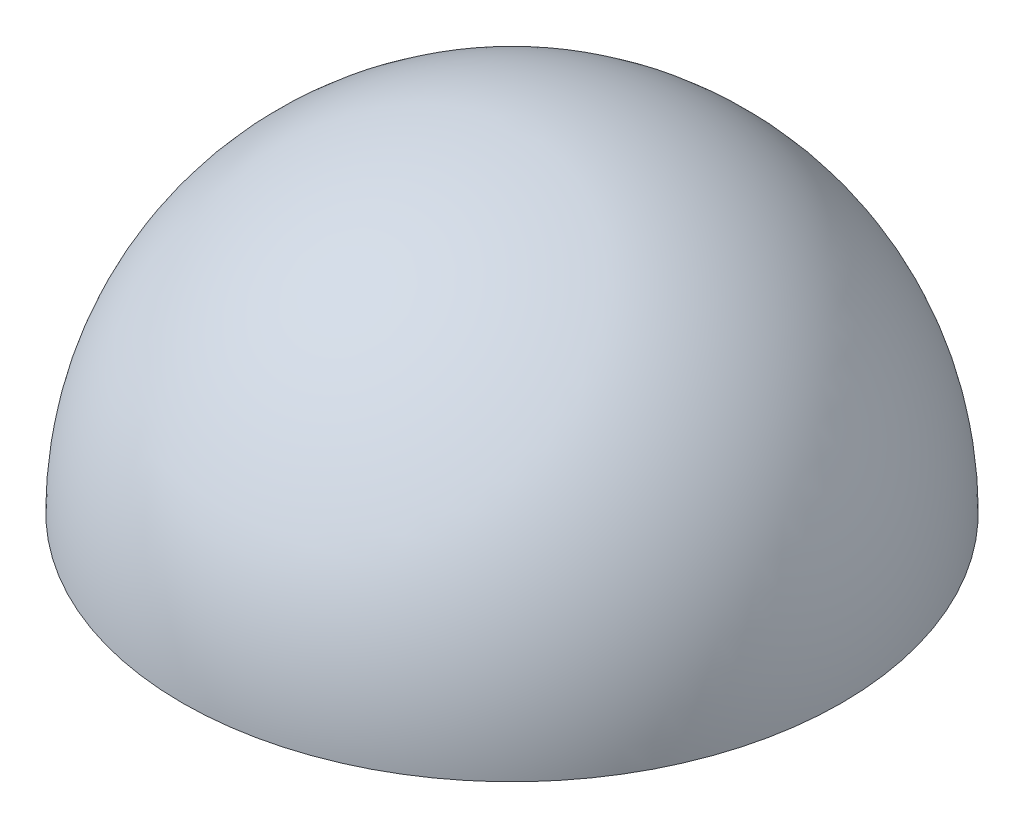
SolidWorks part; units mm, degrees
ref_plane "Front Plane" through (0, 0, 0) normal (0, 0, 1) x (1, 0, 0)
ref_plane "Top Plane" through (0, 0, 0) normal (0, 1, 0) x (1, 0, 0)
ref_plane "Right Plane" through (0, 0, 0) normal (1, 0, 0) x (0, 0, -1)
sketch "Sketch1" plane through (0, 0, 0) normal (0, 0, 1) x (1, 0, 0)
  line L0 (12.5, 0) -> (0, 0)
  line L1 (0, 0) -> (0, 12.5)
  arc A0 (0, 12.5) -> (12.5, 0) centre (0, 0) cw
  dimension "D1" = 12.5
revolve "Revolve1" add sketch "Sketch1" angle 360 about L1
sketch "Sketch2" plane through (0, 0, 0) normal (0, 1, 0) x (1, 0, 0)
  line L0 (0, 9) -> (0, 0) construction
  line L1 (0, 9) -> (-8.5595, 2.7812) construction
  line L2 (-8.5595, 2.7812) -> (-5.2901, -7.2812) construction
  line L3 (-5.2901, -7.2812) -> (5.2901, -7.2812) construction
  line L4 (5.2901, -7.2812) -> (8.5595, 2.7812) construction
  line L5 (8.5595, 2.7812) -> (0, 9) construction
  line L6 (0, 9) -> (2.5562, 3.5183)
  line L7 (2.5562, 3.5183) -> (8.5595, 2.7812)
  line L8 (8.5595, 2.7812) -> (4.136, -1.3439)
  line L9 (4.136, -1.3439) -> (5.2901, -7.2812)
  line L10 (5.2901, -7.2812) -> (0, -4.3488)
  line L11 (0, -4.3488) -> (-5.2901, -7.2812)
  line L12 (-5.2901, -7.2812) -> (-4.136, -1.3439)
  line L13 (-4.136, -1.3439) -> (-8.5595, 2.7812)
  line L14 (-8.5595, 2.7812) -> (-2.5562, 3.5183)
  line L15 (-2.5562, 3.5183) -> (0, 9)
  circle A0 centre (0, 0) radius 7.2812 construction
  dimension "D1" = 50
  dimension "D2" = 9
extrude "Cut-Extrude1" cut sketch "Sketch2" along normal blind 5
